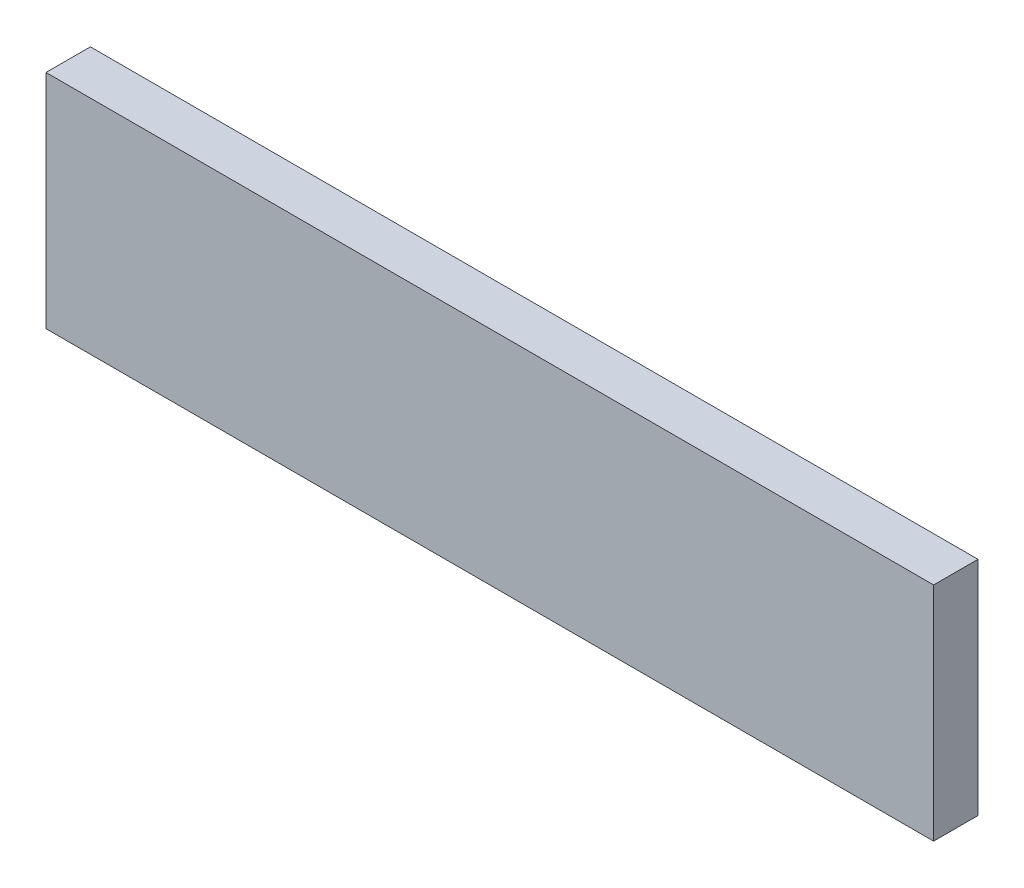
SolidWorks part; units mm, degrees
ref_plane "Front Plane" through (0, 0, 0) normal (0, 0, 1) x (1, 0, 0)
ref_plane "Top Plane" through (0, 0, 0) normal (0, 1, 0) x (1, 0, 0)
ref_plane "Right Plane" through (0, 0, 0) normal (1, 0, 0) x (0, 0, -1)
other "Configuration Table"
sketch "Sketch1" plane through (0, 0, 0) normal (0, 0, 1) x (1, 0, 0)
  line L1 (0, 0) -> (80000, 0)
  line L2 (0, 0) -> (0, 20000)
  line L3 (0, 20000) -> (80000, 20000)
  line L4 (80000, 0) -> (80000, 20000)
  dimension "D1" = 20000
  dimension "D2" = 80000
extrude "Extrude1" add sketch "Sketch1" along normal blind 4000
